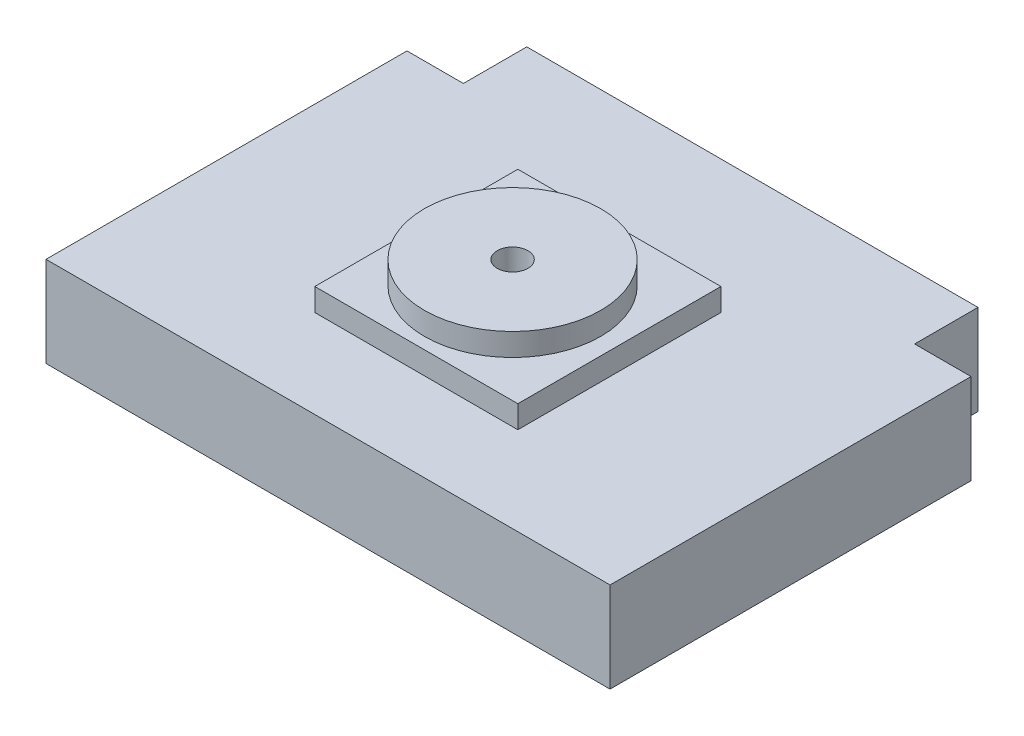
SolidWorks part; units mm, degrees
ref_plane "Front Plane" through (0, 0, 0) normal (0, 0, 1) x (1, 0, 0)
ref_plane "Top Plane" through (0, 0, 0) normal (0, 1, 0) x (1, 0, 0)
ref_plane "Right Plane" through (0, 0, 0) normal (1, 0, 0) x (0, 0, -1)
sketch "Sketch1" plane through (0, 0, 0) normal (0, 1, 0) x (1, 0, 0)
  line L0 (-19.5167, 9.0489) -> (5.8833, 9.0489)
  line L1 (-19.5167, 9.0489) -> (-19.5167, 5.4803)
  line L2 (-19.5167, 5.4803) -> (-22.6917, 5.4803)
  line L3 (-22.6917, 5.4803) -> (-22.6917, -14.8397)
  line L4 (-22.6917, -14.8397) -> (9.0583, -14.8397)
  line L5 (9.0583, -14.8397) -> (9.0583, 5.4803)
  line L6 (9.0583, 5.4803) -> (5.8833, 5.4803)
  line L7 (5.8833, 5.4803) -> (5.8833, 9.0489)
extrude "Boss-Extrude1" add sketch "Sketch1" along normal blind 5.08
sketch "Sketch3" plane through (0, 5.08, 0) normal (0, 1, 0) x (1, 0, 0)
  line L0 (-22.6917, 5.4803) -> (-22.6917, -14.8397) construction
  line L1 (-12.5317, 1.5607) -> (-1.1017, 1.5607)
  line L2 (-12.5317, 1.5607) -> (-12.5317, -9.8693)
  line L3 (-12.5317, -9.8693) -> (-1.1017, -9.8693)
  line L4 (-1.1017, 1.5607) -> (-1.1017, -9.8693)
  line L5 (9.0583, -14.8397) -> (9.0583, 5.4803) construction
  dimension "D1" = 11.43
  dimension "D2" = 11.43
  dimension "D3" = 10.16
  dimension "D4" = 10.16
extrude "Boss-Extrude2" add sketch "Sketch3" along normal blind 1.27
sketch "Sketch5" plane through (0, 6.35, 0) normal (0, 1, 0) x (1, 0, 0)
  circle A0 centre (-7.0092, -4.2587) radius 4.9617
  circle A1 centre (-7.0092, -4.2587) radius 0.8651
extrude "Boss-Extrude3" add sketch "Sketch5" along normal blind 1.27
